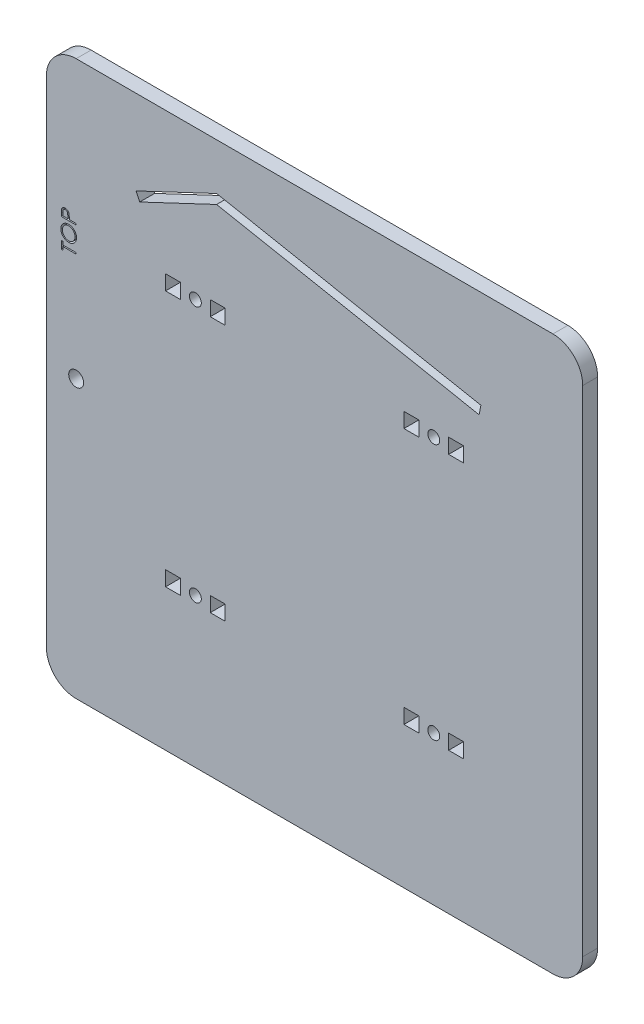
SolidWorks part; units mm, degrees
ref_plane "Plan de face" through (0, 0, 0) normal (0, 0, 1) x (1, 0, 0)
ref_plane "Plan de dessus" through (0, 0, 0) normal (0, 1, 0) x (1, 0, 0)
ref_plane "Plan de droite" through (0, 0, 0) normal (1, 0, 0) x (0, 0, -1)
sketch "Esquisse1" plane through (0, 0, 0) normal (0, 0, 1) x (1, 0, 0)
  line L0 (90, 186) -> (90, 0) construction
  line L1 (0, 0) -> (180, 0)
  line L2 (0, 0) -> (0, 186)
  line L3 (0, 186) -> (180, 186)
  line L4 (180, 0) -> (180, 186)
  line L5 (0, 93) -> (180, 93) construction
  line L6 (10, 93) -> (10, 166) construction
  circle A0 centre (10, 93) radius 2.5
  arc A1 (10, 186) -> (0, 176) centre (10, 176) ccw construction
  text T1 "TOP\r\n"
  point P11 (0, 0)
  line B0 (45, 50) -> (55, 50) construction
  line B1 (45, 52.5) -> (40, 52.5)
  line B2 (45, 52.5) -> (45, 47.5)
  line B3 (45, 47.5) -> (40, 47.5)
  line B4 (40, 52.5) -> (40, 47.5)
  line B5 (55, 52.5) -> (60, 52.5)
  line B6 (55, 52.5) -> (55, 47.5)
  line B7 (55, 47.5) -> (60, 47.5)
  line B8 (60, 52.5) -> (60, 47.5)
  line B9 (50, 50) -> (50, 56.9724) construction
  circle B10 centre (50, 50) radius 2
  line B11 (45, 136) -> (55, 136) construction
  line B12 (45, 138.5) -> (40, 138.5)
  line B13 (45, 138.5) -> (45, 133.5)
  line B14 (45, 133.5) -> (40, 133.5)
  line B15 (40, 138.5) -> (40, 133.5)
  line B16 (55, 138.5) -> (60, 138.5)
  line B17 (55, 138.5) -> (55, 133.5)
  line B18 (55, 133.5) -> (60, 133.5)
  line B19 (60, 138.5) -> (60, 133.5)
  line B20 (50, 136) -> (50, 142.9724) construction
  circle B21 centre (50, 136) radius 2
  line B22 (125, 136) -> (135, 136) construction
  line B23 (125, 138.5) -> (120, 138.5)
  line B24 (125, 138.5) -> (125, 133.5)
  line B25 (125, 133.5) -> (120, 133.5)
  line B26 (120, 138.5) -> (120, 133.5)
  line B27 (135, 138.5) -> (140, 138.5)
  line B28 (135, 138.5) -> (135, 133.5)
  line B29 (135, 133.5) -> (140, 133.5)
  line B30 (140, 138.5) -> (140, 133.5)
  line B31 (130, 136) -> (130, 142.9724) construction
  circle B32 centre (130, 136) radius 2
  line B33 (125, 50) -> (135, 50) construction
  line B34 (125, 52.5) -> (120, 52.5)
  line B35 (125, 52.5) -> (125, 47.5)
  line B36 (125, 47.5) -> (120, 47.5)
  line B37 (120, 52.5) -> (120, 47.5)
  line B38 (135, 52.5) -> (140, 52.5)
  line B39 (135, 52.5) -> (135, 47.5)
  line B40 (135, 47.5) -> (140, 47.5)
  line B41 (140, 52.5) -> (140, 47.5)
  line B42 (130, 50) -> (130, 56.9724) construction
  circle B43 centre (130, 50) radius 2
  dimension "D6" = 5
  dimension "D1" = 81
  dimension "D2" = 80
  dimension "D3" = 50
  dimension "D4" = 50
  dimension "D5" = 180
  dimension "D7" = 10
sketch_block_instance "Trou M4 plots 5mm-1"
sketch_block "Trou M4 plots 5mm" parameters "D2"=4, "D1"=5, "D3"=5, "D4"=10
sketch_block_instance "Trou M4 plots 5mm-2"
sketch_block_instance "Trou M4 plots 5mm-3"
sketch_block_instance "Trou M4 plots 5mm-4"
extrude "Boss.-Extru.1" add sketch "Esquisse1" along normal blind 5 contours L1 L4 L3 L2 B43 B37 B34 B35 B36 B32 B26 B23 B24 B25 B21 B15 B12 B13 B14 B10 B4 B1 B2 B3 A0 B5 B8 B7 B6 B16 B19 B18 B17 B27 B30 B29 B28 B38
fillet "Congé1" radius 10 4 edges at (180, 0, 2.5) (0, 0, 2.5) (0, 186, 2.5) (180, 186, 2.5)
sketch "Esquisse2" plane through (0, 0, 5) normal (0, 0, 1) x (1, 0, 0)
  line L0 (10, 93) -> (10, 176) construction
  line L1 (31.3347, 155.014) -> (57.142, 167.198)
  line L2 (57.142, 167.198) -> (145.2269, 150.1198)
  line L3 (145.2269, 150.1198) -> (145.8213, 153.1851)
  line L4 (145.8213, 153.1851) -> (57.142, 170.3786)
  line L5 (57.142, 170.3786) -> (30.1068, 157.6149)
  line L6 (30.1068, 157.6149) -> (31.3347, 155.014)
  arc A1 (10, 186) -> (0, 176) centre (10, 176) ccw construction
  text T0 "TOP" font "Century Gothic" height 5
  point P10 (0, 0)
  point P11 (0, 0)
  point P14 (0, 0)
  point P15 (0, 0)
extrude "Enlèv. mat.-Extru.1" cut sketch "Esquisse2" against normal through all
